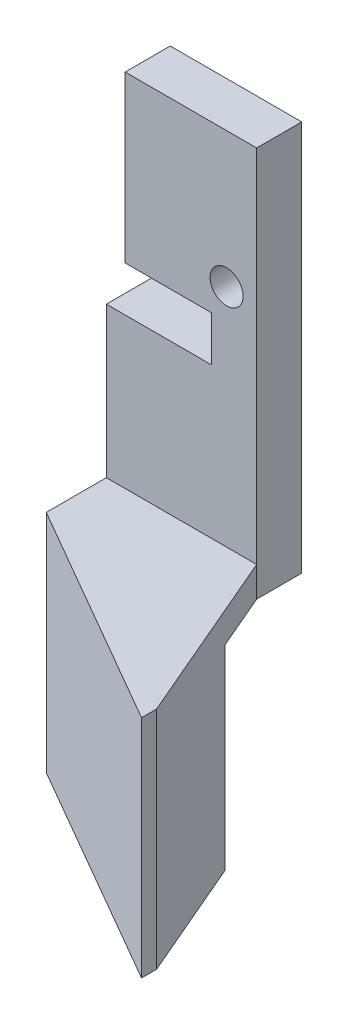
SolidWorks part; units mm, degrees
ref_plane "Front Plane" through (0, 0, 0) normal (0, 0, 1) x (1, 0, 0)
ref_plane "Top Plane" through (0, 0, 0) normal (0, 1, 0) x (1, 0, 0)
ref_plane "Right Plane" through (0, 0, 0) normal (1, 0, 0) x (0, 0, -1)
sketch "Sketch1" plane through (0, 0, 0) normal (0, 0, 1) x (1, 0, 0)
  line L0 (-3.875, 7) -> (-3.875, -7)
  line L1 (4.875, -7) -> (-4.875, -7)
  line L2 (4.875, -7) -> (4.875, 7)
  line L3 (4.875, 7) -> (-4.875, 7)
  line L4 (-4.875, -7) -> (-4.875, 7)
  line L5 (4.875, -7) -> (-4.875, 7) construction
  line L6 (4.875, 7) -> (-4.875, -7) construction
  line L7 (1.875, -7) -> (-4.875, -7)
  line L8 (1.875, -7) -> (1.875, -4)
  line L9 (1.875, -4) -> (-4.875, -4)
  line L10 (-4.875, -7) -> (-4.875, -4)
  circle A0 centre (2.875, -2) radius 1.1
  point P0 (0, 0)
  dimension "D1" = 2.2
  dimension "D2" = 5
  dimension "D3" = 2
  dimension "D4" = 3
  dimension "D5" = 3
  dimension "D6" = 9.75
  dimension "D7" = 14
  dimension "D8" = 1
extrude "Boss-Extrude1" add sketch "Sketch1" along normal blind 3 contours L9 L8 L1 L2 L3 L0 A0
sketch "Sketch2" plane through (0, 0, 3) normal (0, 0, 1) x (1, 0, 0)
  line L1 (4.875, -7) -> (-5.125, -7)
  line L2 (4.875, -7) -> (4.875, -32)
  line L3 (4.875, -32) -> (-5.125, -32)
  line L4 (-5.125, -7) -> (-5.125, -32)
  dimension "D1" = 25
  dimension "D2" = 10
extrude "Boss-Extrude2" add sketch "Sketch2" against normal blind 3
sketch "Sketch3" plane through (0, -32, 0) normal (0, -1, 0) x (-1, 0, 0)
  line L0 (5.125, -3) -> (-9.875, -11.6603)
  line L1 (5.125, 0) -> (-9.875, 0)
  line L2 (5.125, 0) -> (5.125, -3)
  line L3 (5.125, -3) -> (-9.875, -3)
  line L4 (-9.875, 0) -> (-9.875, -3)
  line L5 (-9.875, -3) -> (-9.875, -11.6603)
  line L6 (5.125, -3) -> (-9.875, -11.6603)
  line L7 (5.125, -3) -> (5.125, -7)
  line L8 (-9.875, -11.6603) -> (-9.875, -15.6603)
  line L9 (5.125, -7) -> (-9.875, -15.6603)
  line M7 (-4.875, -3) -> (5.125, -3)
  line M8 (5.125, -3) -> (5.125, 0)
  line M9 (5.125, 0) -> (-4.875, 0)
  line M10 (-4.875, 0) -> (-4.875, -3)
  dimension "D1" = 15
  dimension "D2" = 30
  dimension "D3" = 4
extrude "Boss-Extrude3" add sketch "Sketch3" against normal blind 15 contours L3 L5 L0 M7 | L1 L4 L3 M10 | M10 M7 M8 M9 | L9 L7 L0 L8
sketch "Sketch5" plane through (0, -17, 0) normal (0, 1, 0) x (1, 0, 0)
  line L0 (9.875, -14.6603) -> (4.875, -3)
  line L1 (9.875, 0) -> (9.875, -15.6603) construction
  line L2 (9.875, -14.6603) -> (9.875, 0)
  line L3 (9.875, 0) -> (4.875, 0)
  line L4 (4.875, 0) -> (4.875, -3)
  dimension "D1" = 1
extrude "Cut-Extrude1" cut sketch "Sketch5" against normal blind 15
sketch "Sketch6" plane through (0, -32, 0) normal (0, -1, 0) x (-1, 0, 0)
  line L0 (5.125, 0) -> (-6.4556, -6.6861)
  line L1 (-4.875, -3) -> (-9.875, -14.6603) construction
  line L2 (5.125, -7) -> (-9.875, -15.6603) construction
  line L9 (-4.875, -3) -> (-9.875, -14.6603)
  line L10 (-9.875, -14.6603) -> (-9.875, -15.6603)
  line L11 (-9.875, -15.6603) -> (5.125, -7)
  line L12 (5.125, -7) -> (5.125, 0)
  line L13 (5.125, 0) -> (-4.875, 0)
  line L14 (-4.875, 0) -> (-4.875, -3)
  line L15 (-4.875, -3) -> (-9.875, -14.6603)
  line L16 (-9.875, -14.6603) -> (-9.875, -15.6603)
  line L17 (-9.875, -15.6603) -> (5.125, -7)
  line L18 (5.125, -7) -> (5.125, 0)
  line L19 (5.125, 0) -> (-4.875, 0)
  line L20 (-4.875, 0) -> (-4.875, -3)
  line M8 (-4.875, -3) -> (-9.875, -14.6603)
  line M12 (5.125, 0) -> (-4.875, 0)
  line M13 (-4.875, 0) -> (-4.875, -3)
  dimension "D1" = 0
extrude "Cut-Extrude3" cut sketch "Sketch6" against normal blind 13 contours L0 M12 M13 M8
